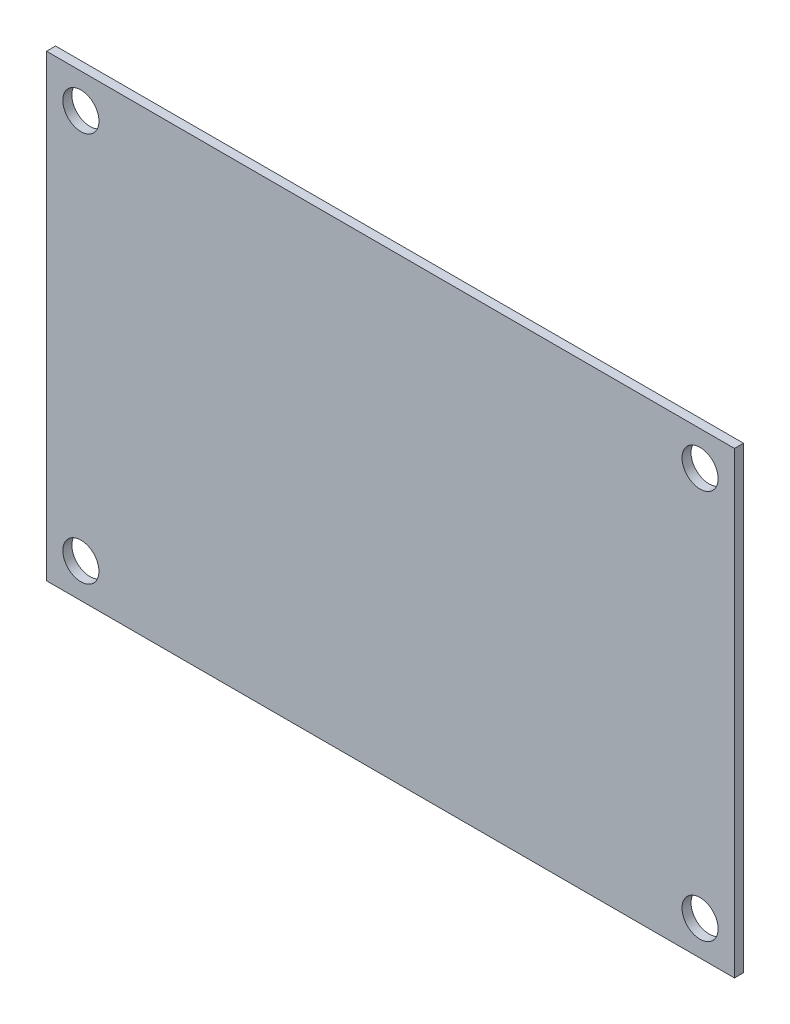
SolidWorks part; units mm, degrees
ref_plane "前视基准面" through (0, 0, 0) normal (0, 0, 1) x (1, 0, 0)
ref_plane "上视基准面" through (0, 0, 0) normal (0, 1, 0) x (1, 0, 0)
ref_plane "右视基准面" through (0, 0, 0) normal (1, 0, 0) x (0, 0, -1)
sketch "Sketch1" plane through (0, 0, 0) normal (0, 0, 1) x (1, 0, 0)
  line L0 (0, 3.8556) -> (0, -4.4482) construction
  line L1 (38.1, -25.4) -> (-38.1, -25.4)
  line L2 (38.1, -25.4) -> (38.1, 25.4)
  line L3 (38.1, 25.4) -> (-38.1, 25.4)
  line L4 (-38.1, -25.4) -> (-38.1, 25.4)
  line L5 (38.1, -25.4) -> (-38.1, 25.4) construction
  line L6 (38.1, 25.4) -> (-38.1, -25.4) construction
  line L7 (-4.5978, 0) -> (5.9439, 0) construction
  circle A0 centre (-34.29, 21.59) radius 2
  circle A1 centre (34.29, 21.59) radius 2
  circle A2 centre (-34.29, -21.59) radius 2
  circle A3 centre (34.29, -21.59) radius 2
  point P0 (0, 0)
  dimension "D4" = 4
  dimension "D1" = 76.2
  dimension "D2" = 50.8
  dimension "D3" = 3.81
  dimension "D5" = 3.81
extrude "Boss-Extrude1" add sketch "Sketch1" along normal blind 1
